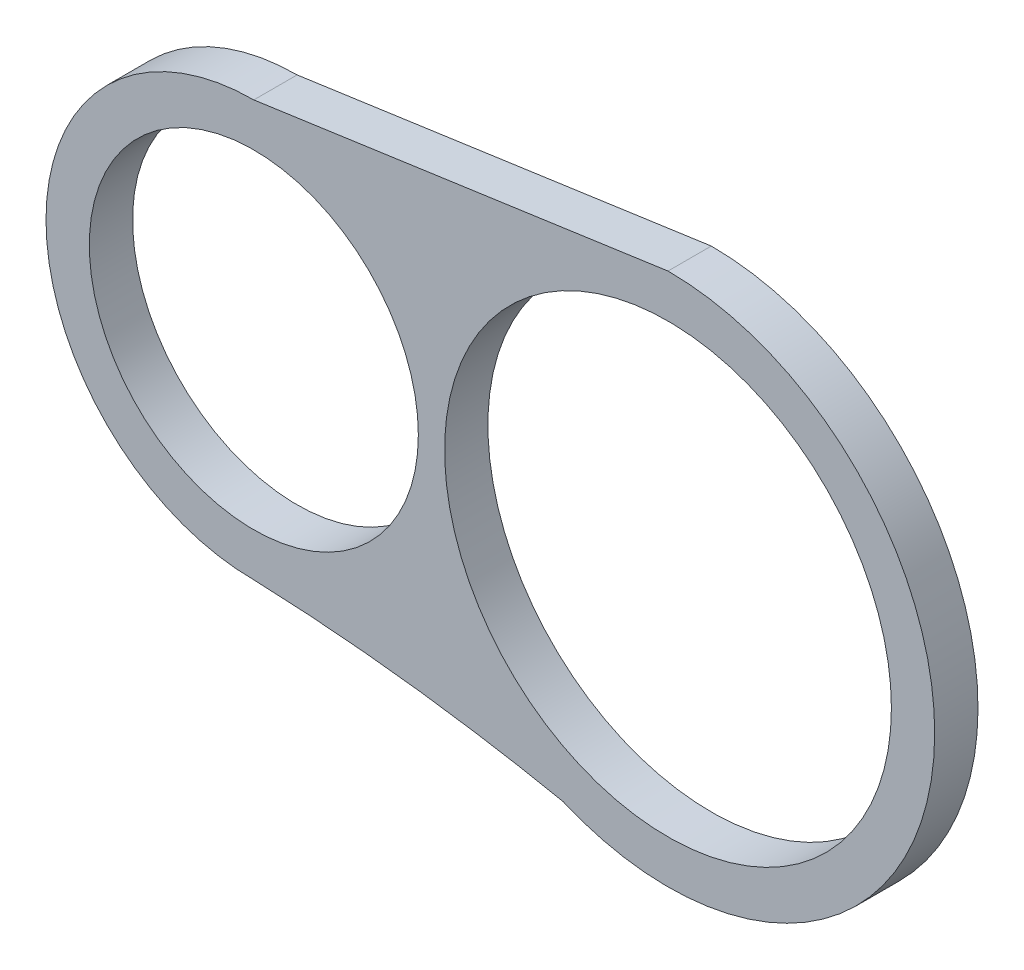
SolidWorks part; units mm, degrees
ref_plane "Plano frontal" through (0, 0, 0) normal (0, 0, 1) x (1, 0, 0)
ref_plane "Plano superior" through (0, 0, 0) normal (0, 1, 0) x (1, 0, 0)
ref_plane "Plano direito" through (0, 0, 0) normal (1, 0, 0) x (0, 0, -1)
sketch "Esboço1" plane through (0, 0, 0) normal (0, 0, 1) x (1, 0, 0)
  line L0 (-23.915, 0) -> (23.915, 0) construction
  circle A0 centre (23.915, 0) radius 25.8
  circle A1 centre (-23.915, 0) radius 19
  arc A2 (-23.915, 24) -> (-23.915, -24) centre (-23.915, 0) ccw
  arc A3 (11.8021, -28.3182) -> (23.915, 30.8) centre (23.915, 0) ccw
  circle A4 centre (23.915, 0) radius 30.8 construction
  circle A5 centre (-23.915, 0) radius 24 construction
  spline S0 degree 1 poles (23.915, 30.8) (-23.915, 24) knots 0 0 1 1
  spline S1 degree 2 poles (-23.915, -24) (-6.0564, -24.6591) (11.8021, -28.3182) knots 0 0 0 0.746752 0.746752 0.746752
  point P4 (0, 0)
  dimension "D1" = 5
extrude "Ressalto-extrusão1" add sketch "Esboço1" along normal blind 5
